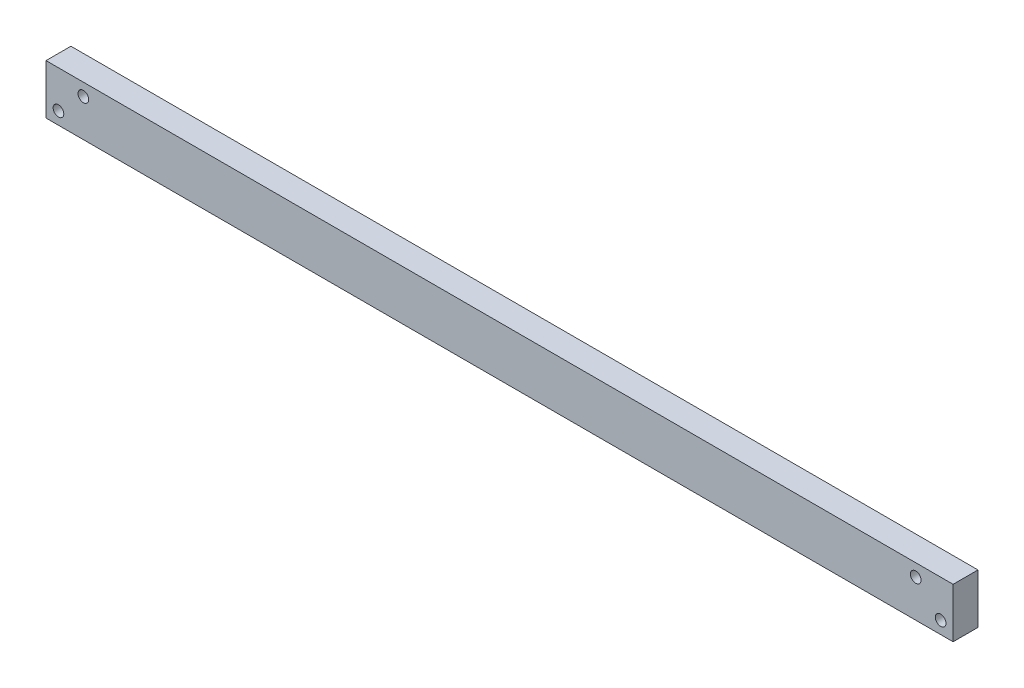
SolidWorks part; units mm, degrees
ref_plane "Ön Düzlem" through (0, 0, 0) normal (0, 0, 1) x (1, 0, 0)
ref_plane "Üst Düzlem" through (0, 0, 0) normal (0, 1, 0) x (1, 0, 0)
ref_plane "Sağ Düzlem" through (0, 0, 0) normal (1, 0, 0) x (0, 0, -1)
sketch "Çizim1" plane through (0, 0, 0) normal (0, 0, 1) x (1, 0, 0)
  line L1 (-255, -14) -> (255, -14)
  line L2 (-255, -14) -> (-255, 14)
  line L3 (-255, 14) -> (255, 14)
  line L4 (255, -14) -> (255, 14)
  line L5 (-255, -14) -> (255, 14) construction
  line L6 (-255, 14) -> (255, -14) construction
  point P0 (0, 0)
  dimension "D1" = 510
  dimension "D2" = 28
extrude "Yükseklik-Ekstrüzyon1" add sketch "Çizim1" along normal blind 14
sketch "Çizim2" plane through (0, 0, 14) normal (0, 0, 1) x (1, 0, 0)
  line L0 (-227, 14) -> (-227, -14) construction
  line L1 (-255, 14) -> (-255, -14) construction
  line L2 (255, 14) -> (-255, 14) construction
  line L3 (-248, 7) -> (-234, 7) construction
  line L4 (-248, 7) -> (-248, -7) construction
  line L5 (-248, -7) -> (-234, -7) construction
  line L6 (-234, 7) -> (-234, -7) construction
  line L7 (-248, 7) -> (-234, -7) construction
  line L8 (-248, -7) -> (-234, 7) construction
  line L9 (-255, -14) -> (255, -14) construction
  line L10 (-255, -14) -> (-227, -14) construction
  line L11 (0, 64.6485) -> (0, -64.6485) construction
  circle A0 centre (-234, 7) radius 3
  circle A1 centre (-248, -7) radius 3
  circle A2 centre (248, -7) radius 3
  circle A3 centre (234, 7) radius 3
  point P4 (-241, -14)
  point P8 (-241, 0)
  point P22 (-227, 0)
  point P23 (0, 0)
  dimension "D2" = 6
  dimension "D1" = 28
  dimension "D3" = 14
extrude "Kes-Ekstrüzyon1" cut sketch "Çizim2" against normal up to next
